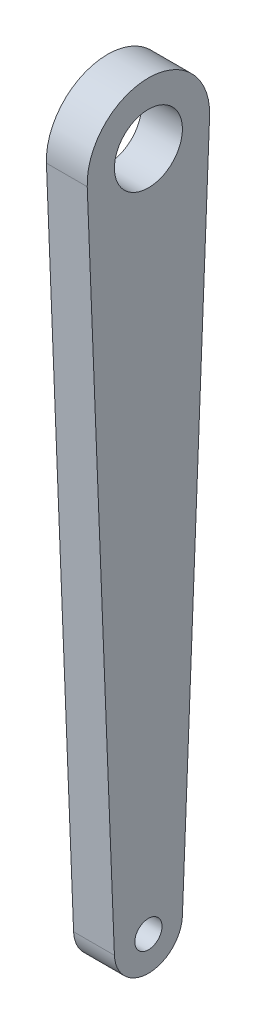
SolidWorks part; units mm, degrees
ref_plane "Front Plane" through (0, 0, 0) normal (0, 0, 1) x (1, 0, 0)
ref_plane "Top Plane" through (0, 0, 0) normal (0, 1, 0) x (1, 0, 0)
ref_plane "Right Plane" through (0, 0, 0) normal (1, 0, 0) x (0, 0, -1)
sketch "Sketch1" plane through (0, 0, 0) normal (1, 0, 0) x (0, 0, -1)
  line L0 (-4.4964, -0.18) -> (-2.498, -50.1)
  line L1 (0, 0) -> (0, -21.1391) construction
  line L2 (4.4964, -0.18) -> (2.498, -50.1)
  circle A0 centre (0, 0) radius 2.5
  arc A1 (4.4964, -0.18) -> (-4.4964, -0.18) centre (0, 0) ccw
  arc A2 (-2.498, -50.1) -> (2.498, -50.1) centre (0, -50) ccw
  circle A3 centre (0, -50) radius 1
  dimension "D1" = 5
  dimension "D2" = 9
  dimension "D3" = 5
  dimension "D4" = 2
  dimension "D5" = 0
  dimension "D6" = 50
extrude "Boss-Extrude1" add sketch "Sketch1" along normal blind 3
